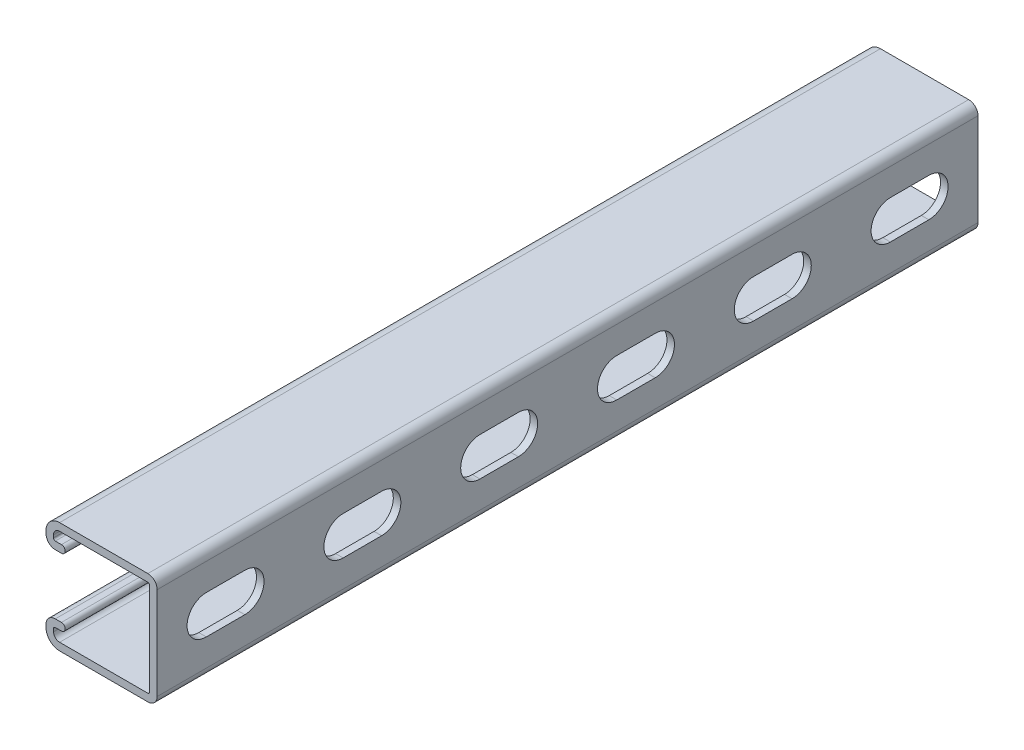
SolidWorks part; units mm, degrees
ref_plane "Front Plane" through (0, 0, 0) normal (0, 0, 1) x (1, 0, 0)
ref_plane "Top Plane" through (0, 0, 0) normal (0, 1, 0) x (1, 0, 0)
ref_plane "Right Plane" through (0, 0, 0) normal (1, 0, 0) x (0, 0, -1)
sketch "Sketch1" plane through (0, 0, 0) normal (0, 0, 1) x (1, 0, 0)
  line L0 (0, 0) -> (-41.275, 0) construction
  line L3 (-41.275, 20.6375) -> (0, 20.6375) construction
  line L4 (-41.275, 20.6375) -> (-41.275, -20.6375) construction
  line L5 (-41.275, -20.6375) -> (0, -20.6375) construction
  line L6 (0, 20.6375) -> (0, -20.6375) construction
  line L7 (-36.2267, 20.6375) -> (-3.4607, 20.6375)
  line L8 (0, 17.1767) -> (0, -17.1767)
  line L9 (-2.794, -17.1767) -> (-2.794, 17.1767)
  line L10 (-3.4608, 17.8435) -> (-36.2267, 17.8435)
  line L11 (-41.275, 15.5892) -> (-41.275, 14.5732)
  line L12 (-37.8142, 11.1125) -> (-35.5346, 11.1125)
  line L14 (-35.5346, 13.9065) -> (-37.8142, 13.9065)
  line L15 (-38.481, 14.5732) -> (-38.481, 15.5892)
  line L16 (-38.481, -14.5733) -> (-38.481, -15.5893)
  line L17 (-35.5346, -13.9065) -> (-37.8142, -13.9065)
  line L18 (-37.8142, -11.1125) -> (-35.5346, -11.1125)
  line L19 (-41.275, -15.5893) -> (-41.275, -14.5733)
  line L20 (-3.4607, -17.8435) -> (-36.2267, -17.8435)
  line L21 (-36.2267, -20.6375) -> (-3.4607, -20.6375)
  line L22 (-2.794, -20.6375) -> (-2.794, 20.6375) construction
  arc A1 (0, 17.1767) -> (-3.4607, 20.6375) centre (-3.4607, 17.1767) ccw
  arc A2 (-2.794, 17.1767) -> (-3.4608, 17.8435) centre (-3.4607, 17.1767) ccw
  arc A4 (-36.2267, 20.6375) -> (-41.275, 15.5892) centre (-36.2267, 15.5892) ccw
  arc A5 (-41.275, 14.5732) -> (-37.8142, 11.1125) centre (-37.8142, 14.5732) ccw
  arc A6 (-35.5346, 11.1125) -> (-35.5346, 13.9065) centre (-35.5346, 12.5095) ccw
  arc A7 (-37.8142, 13.9065) -> (-38.481, 14.5732) centre (-37.8142, 14.5732) cw
  arc A8 (-38.481, 15.5892) -> (-36.2267, 17.8435) centre (-36.2267, 15.5892) cw
  arc A9 (-38.481, -15.5893) -> (-36.2267, -17.8435) centre (-36.2267, -15.5893) ccw
  arc A10 (-37.8142, -13.9065) -> (-38.481, -14.5733) centre (-37.8142, -14.5733) ccw
  arc A11 (-35.5346, -11.1125) -> (-35.5346, -13.9065) centre (-35.5346, -12.5095) cw
  arc A12 (-41.275, -14.5733) -> (-37.8142, -11.1125) centre (-37.8142, -14.5733) cw
  arc A13 (-36.2267, -20.6375) -> (-41.275, -15.5893) centre (-36.2267, -15.5893) cw
  arc A14 (-2.794, -17.1767) -> (-3.4607, -17.8435) centre (-3.4607, -17.1767) cw
  arc A15 (0, -17.1767) -> (-3.4607, -20.6375) centre (-3.4607, -17.1767) cw
  point P24 (0, 20.6375)
  point P65 (-2.794, 0)
  dimension "D1" = 3.4608
  dimension "D2" = 5.0482
  dimension "D3" = 3.4608
  dimension "Ht." = 41.275
  dimension "Wd." = 41.275
  dimension "Thk." = 2.794
  dimension "D4" = 9.525
  dimension "D5" = 7.1374
extrude "Boss-Extrude1" add sketch "Sketch1" against normal blind 304.8
sketch "Sketch3" plane through (0, 0, 0) normal (1, 0, 0) x (0, 0, -1)
  line L0 (0, 0) -> (304.8, 0) construction
  point P2 (101.6, 0)
  point P3 (203.2, 0)
  dimension "D1" = 101.6
  dimension "D2" = 101.6
  dimension "D3" = 304.8
sketch "Sketch2" plane through (0, 0, 0) normal (1, 0, 0) x (0, 0, -1)
  line L0 (18.2562, 0) -> (32.5437, 0) construction
  line L1 (18.2562, 7.1437) -> (32.5437, 7.1437)
  line L2 (18.2562, -7.1437) -> (32.5437, -7.1437)
  line L3 (18.2562, 0) -> (0, 0) construction
  line L4 (25.4, 0) -> (76.2, 0) construction
  line L5 (0, -17.1767) -> (0, 17.1767) construction
  arc A0 (18.2562, 7.1437) -> (18.2562, -7.1437) centre (18.2562, 0) ccw
  arc A1 (32.5437, -7.1437) -> (32.5437, 7.1437) centre (32.5437, 0) ccw
  point P3 (25.4, 0)
  dimension "Hole to End" = 11.1125
  dimension "D2" = 25.4
extrude "Cut-Extrude1" cut sketch "Sketch2" against normal up to vertex (2.794 mm away) up to point (-2.794, 0, 0)
pattern_linear "LPattern1" count 6 spacing 50.8 along (0, 0, -1) of "Cut-Extrude1"
equation "\"D1@LPattern1\" = \"Slot Ctr.@Sketch2\""
equation "\"Hole Count@LPattern1\" = \"Lg.@Boss-Extrude1\" / \"D1@LPattern1\""
equation "\"D3@Sketch3\" = \"Lg.@Boss-Extrude1\""
